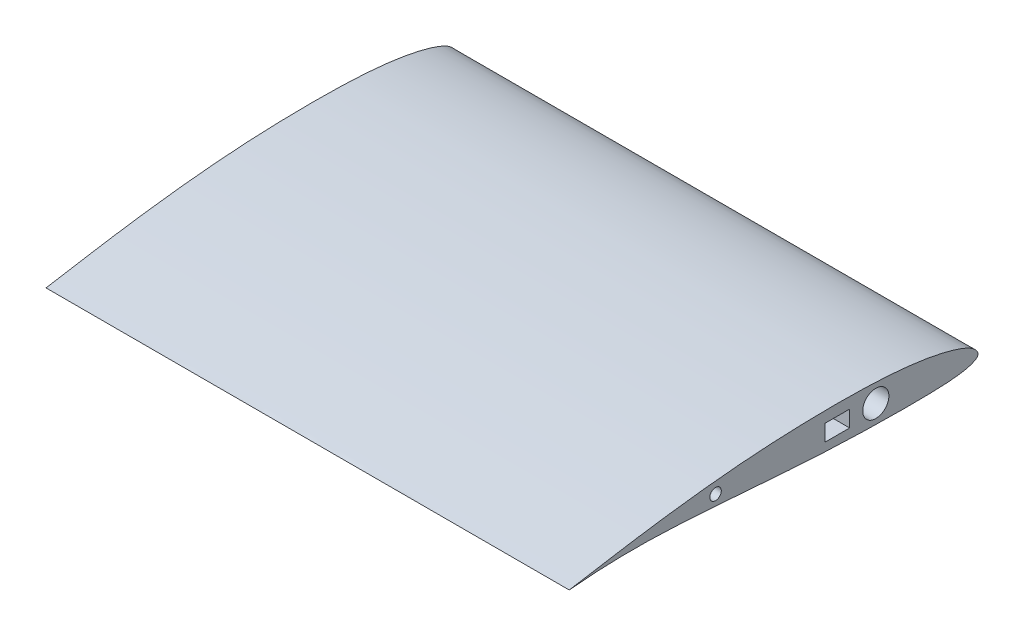
SolidWorks part; units mm, degrees
material "Foam"
ref_plane "Piano frontale" through (0, 0, 0) normal (0, 0, 1) x (1, 0, 0)
ref_plane "Piano superiore" through (0, 0, 0) normal (0, 1, 0) x (1, 0, 0)
ref_plane "Piano destro" through (0, 0, 0) normal (1, 0, 0) x (0, 0, -1)
curve "Curva1"
  spline degree 3 poles (0, 0.1724, 248.285) (0, -0.053, 250.4273) (0, 0.2462, 248.3284) (0, 0.5529, 246.6445) (0, 1.2459, 242.6221) (0, 2.0989, 237.7464) (0, 3.1818, 231.3634) (0, 4.2933, 223.9772) (0, 5.7312, 215.5604) (0, 7.1315, 206.3004) (0, 8.6324, 196.1631) (0, 10.1162, 185.3524) (0, 11.5493, 173.9891) (0, 12.8816, 162.1914) (0, 14.0593, 150.0724) (0, 15.0523, 137.7438) (0, 15.8256, 125.3116) (0, 16.3834, 112.8888) (0, 16.7267, 100.597) (0, 16.8648, 88.5669) (0, 16.792, 76.9314) (0, 16.4941, 65.8165) (0, 15.9609, 55.3329) (0, 15.1594, 45.573) (0, 14.0978, 36.6074) (0, 12.7884, 28.4972) (0, 11.2839, 21.2988) (0, 9.6413, 15.0749) (0, 7.9136, 9.8809) (0, 6.1182, 5.7699) (0, 4.2384, 2.7289) (0, 2.3057, 0.8126) (0, 0.7927, 0.0312) (0, -0.4105, -0.0213) (0, -1.7115, 0.4949) (0, -2.8658, 2.6253) (0, -4.0404, 5.6977) (0, -4.9287, 10.0719) (0, -5.5974, 15.6262) (0, -6.0122, 22.4122) (0, -6.265, 30.3619) (0, -6.3814, 39.3972) (0, -6.3554, 49.3987) (0, -6.2185, 60.2453) (0, -5.9476, 71.8018) (0, -5.5368, 83.9408) (0, -4.9386, 96.5461) (0, -4.1527, 109.5201) (0, -3.2196, 122.7671) (0, -2.1909, 136.1764) (0, -1.148, 149.6158) (0, -0.1602, 162.9314) (0, 0.706, 175.9537) (0, 1.3896, 188.4999) (0, 1.8332, 200.3712) (0, 1.9676, 211.3376) (0, 1.8232, 221.1842) (0, 1.4973, 229.6804) (0, 1.0741, 236.8065) (0, 0.6857, 242.1894) (0, 0.3087, 246.5181) (0, 0.1724, 248.285) (0, -0.053, 250.4273) (0, 0.2462, 248.3284) knots -0.014202 -0.006329 -0.001589 0 0.001576 0.006211 0.01368 0.023764 0.036307 0.051658 0.068045 0.086769 0.107053 0.128647 0.151303 0.174786 0.19886 0.223309 0.247929 0.272522 0.296848 0.320648 0.343669 0.365658 0.3864 0.405741 0.423561 0.439779 0.454311 0.467034 0.477831 0.486643 0.493542 0.498786 0.50271 0.50309 0.505896 0.510322 0.516831 0.525521 0.536535 0.549945 0.565696 0.583577 0.603379 0.624844 0.647727 0.671743 0.696673 0.722357 0.748609 0.77521 0.801891 0.828329 0.854175 0.879074 0.902636 0.924421 0.943939 0.960827 0.974827 0.985798 0.993671 0.998411 1 1.001576 1.006211 1.01368 periodic
sketch "Schizzo1" plane through (0, 0, 0) normal (1, 0, 0) x (0, 0, -1)
  line L0 (-250, 0) -> (0.0001, 0.0174) construction
  line L1 (0.0001, 0.0174) -> (-0.0034, 50.0174) construction
  line L2 (-62.4999, 16.3096) -> (-62.4999, -6.155) construction
  line L4 (-78.4999, 10.0773) -> (-93.4999, 10.0773)
  line L5 (-78.4999, 10.0773) -> (-78.4999, 0.0773)
  line L6 (-78.4999, 0.0773) -> (-93.4999, 0.0773)
  line L7 (-93.4999, 10.0773) -> (-93.4999, 0.0773)
  circle A0 centre (-62.4999, 5.0773) radius 8
  spline S0 degree 3 poles (-248.3284, 0.2462) (-250.4273, -0.053) (-248.285, 0.1724) (-246.5181, 0.3087) (-242.1894, 0.6857) (-236.8065, 1.0741) (-229.6804, 1.4973) (-221.1842, 1.8232) (-211.3376, 1.9676) (-200.3712, 1.8332) (-188.4999, 1.3896) (-175.9537, 0.706) (-162.9314, -0.1602) (-149.6158, -1.148) (-136.1764, -2.1909) (-122.7671, -3.2196) (-109.5201, -4.1527) (-96.5461, -4.9386) (-83.9408, -5.5368) (-71.8018, -5.9476) (-60.2453, -6.2185) (-49.3987, -6.3554) (-39.3972, -6.3814) (-30.3619, -6.265) (-22.4122, -6.0122) (-15.6262, -5.5974) (-10.0719, -4.9287) (-5.6977, -4.0404) (-2.6253, -2.8658) (-0.4949, -1.7115) (0.0213, -0.4105) (-0.0312, 0.7927) (-0.8126, 2.3057) (-2.7289, 4.2384) (-5.7699, 6.1182) (-9.8809, 7.9136) (-15.0749, 9.6413) (-21.2988, 11.2839) (-28.4972, 12.7884) (-36.6074, 14.0978) (-45.573, 15.1594) (-55.3329, 15.9609) (-65.8165, 16.4941) (-76.9314, 16.792) (-88.5669, 16.8648) (-100.597, 16.7267) (-112.8888, 16.3834) (-125.3116, 15.8256) (-137.7438, 15.0523) (-150.0724, 14.0593) (-162.1914, 12.8816) (-173.9891, 11.5493) (-185.3524, 10.1162) (-196.1631, 8.6324) (-206.3004, 7.1315) (-215.5604, 5.7312) (-223.9772, 4.2933) (-231.3634, 3.1818) (-237.7464, 2.0989) (-242.6221, 1.2459) (-246.6445, 0.5529) (-248.3284, 0.2462) (-250.4273, -0.053) (-248.285, 0.1724) knots -0.01368 -0.006211 -0.001576 0 0.001589 0.006329 0.014202 0.025173 0.039173 0.056061 0.075579 0.097364 0.120926 0.145825 0.171671 0.198109 0.22479 0.251391 0.277643 0.303327 0.328257 0.352273 0.375156 0.396621 0.416423 0.434304 0.450055 0.463465 0.474479 0.483169 0.489678 0.494104 0.49691 0.49729 0.501214 0.506458 0.513357 0.522169 0.532966 0.545689 0.560221 0.576439 0.594259 0.6136 0.634342 0.656331 0.679352 0.703152 0.727478 0.752071 0.776691 0.80114 0.825214 0.848697 0.871353 0.892947 0.913231 0.931955 0.948342 0.963693 0.976236 0.98632 0.993789 0.998424 1 1.001589 1.006329 1.014202 only from (-250, 0) to (-250, 0) construction
  spline S1 degree 3 poles (-248.3284, 0.2462) (-250.4273, -0.053) (-248.285, 0.1724) (-246.5181, 0.3087) (-242.1894, 0.6857) (-236.8065, 1.0741) (-229.6804, 1.4973) (-221.1842, 1.8232) (-211.3376, 1.9676) (-200.3712, 1.8332) (-188.4999, 1.3896) (-175.9537, 0.706) (-162.9314, -0.1602) (-149.6158, -1.148) (-136.1764, -2.1909) (-122.7671, -3.2196) (-109.5201, -4.1527) (-96.5461, -4.9386) (-83.9408, -5.5368) (-71.8018, -5.9476) (-60.2453, -6.2185) (-49.3987, -6.3554) (-39.3972, -6.3814) (-30.3619, -6.265) (-22.4122, -6.0122) (-15.6262, -5.5974) (-10.0719, -4.9287) (-5.6977, -4.0404) (-2.6253, -2.8658) (-0.4949, -1.7115) (0.0213, -0.4105) (-0.0312, 0.7927) (-0.8126, 2.3057) (-2.7289, 4.2384) (-5.7699, 6.1182) (-9.8809, 7.9136) (-15.0749, 9.6413) (-21.2988, 11.2839) (-28.4972, 12.7884) (-36.6074, 14.0978) (-45.573, 15.1594) (-55.3329, 15.9609) (-65.8165, 16.4941) (-76.9314, 16.792) (-88.5669, 16.8648) (-100.597, 16.7267) (-112.8888, 16.3834) (-125.3116, 15.8256) (-137.7438, 15.0523) (-150.0724, 14.0593) (-162.1914, 12.8816) (-173.9891, 11.5493) (-185.3524, 10.1162) (-196.1631, 8.6324) (-206.3004, 7.1315) (-215.5604, 5.7312) (-223.9772, 4.2933) (-231.3634, 3.1818) (-237.7464, 2.0989) (-242.6221, 1.2459) (-246.6445, 0.5529) (-248.3284, 0.2462) (-250.4273, -0.053) (-248.285, 0.1724) knots -0.01368 -0.006211 -0.001576 0 0.001589 0.006329 0.014202 0.025173 0.039173 0.056061 0.075579 0.097364 0.120926 0.145825 0.171671 0.198109 0.22479 0.251391 0.277643 0.303327 0.328257 0.352273 0.375156 0.396621 0.416423 0.434304 0.450055 0.463465 0.474479 0.483169 0.489678 0.494104 0.49691 0.49729 0.501214 0.506458 0.513357 0.522169 0.532966 0.545689 0.560221 0.576439 0.594259 0.6136 0.634342 0.656331 0.679352 0.703152 0.727478 0.752071 0.776691 0.80114 0.825214 0.848697 0.871353 0.892947 0.913231 0.931955 0.948342 0.963693 0.976236 0.98632 0.993789 0.998424 1 1.001589 1.006329 1.014202 only from (-250, 0) to (-250, 0)
  point P11 (-78.4999, 5.0773)
  dimension "D3" = 16
  dimension "D1" = 50
  dimension "D2" = 62.5
  dimension "D4" = 15
  dimension "D5" = 10
  dimension "D6" = 16
extrude "CorpoFoam" add sketch "Schizzo1" along normal blind 320
sketch "Schizzo2" plane through (0, 0, 0) normal (-1, 0, 0) x (0, 0, 1)
  line L1 (62.4999, 5.0773) -> (160.4999, 6.0773) construction
  circle A0 centre (160.4999, 6.0773) radius 3.5
  dimension "D1" = 7
  dimension "D2" = 98
  dimension "D3" = 1
extrude "ForoCentinaSinistra" cut sketch "Schizzo2" against normal blind 15
sketch "Schizzo3" plane through (320, 0, 0) normal (1, 0, 0) x (0, 0, -1)
  circle A0 centre (-160.4999, 6.0773) radius 3.5
  dimension "D1" = 7
extrude "ForoCentianDestra" cut sketch "Schizzo3" against normal blind 15
